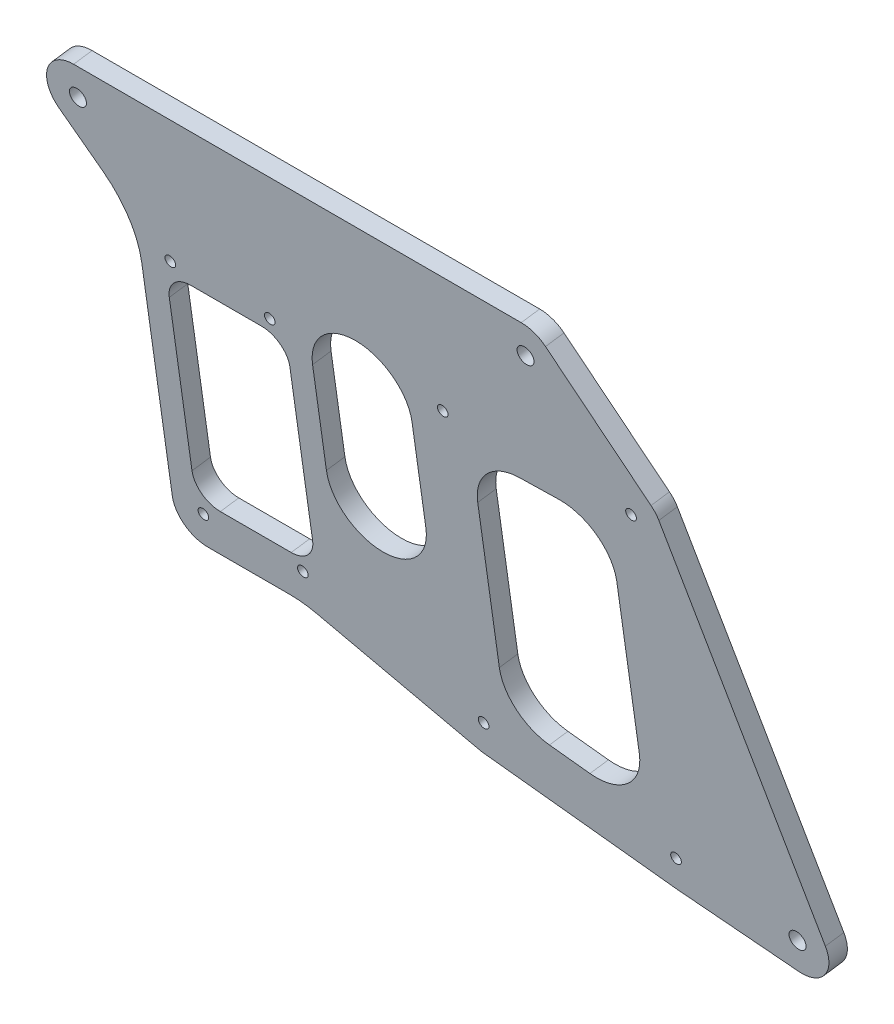
SolidWorks part; units mm, degrees
material "Acrylic (Medium-high impact)"
ref_plane "Front Plane" through (0, 0, 0) normal (0, 0, 1) x (1, 0, 0)
ref_plane "Top Plane" through (0, 0, 0) normal (0, 1, 0) x (1, 0, 0)
ref_plane "Right Plane" through (0, 0, 0) normal (1, 0, 0) x (0, 0, -1)
sketch "Sketch2" plane through (0, -851.6064, 6059.4947) normal (0, 0.1392, -0.9903) x (-1, 0, 0)
  line L1 (-291.6598, -2420.9907) -> (-107.4887, -2420.9907)
  line L2 (-291.6598, -2420.9907) -> (-291.6598, -2293.9907)
  line L3 (-291.6598, -2293.9907) -> (-107.4887, -2293.9907)
  line L4 (-107.4887, -2420.9907) -> (-107.4887, -2293.9907)
  circle A0 centre (-283.7223, -2413.0532) radius 2.1526 construction
  circle A1 centre (-115.4262, -2301.9282) radius 2.1526 construction
  dimension "D3" = 7.9375
  dimension "D2" = 7.9375
  dimension "D1" = 127
  dimension "D4" = 7.9375
extrude "Boss-Extrude1" add sketch "Sketch2" along normal blind 4.7625
hole_wizard "CSK for #6 Flat Head Machine Screw (100)1" positions "Sketch3" profile "Sketch4" countersink size "#6" standard "ANSI Inch" end condition through all
sketch "Sketch3" plane through (0, -850.9436, 6054.7786) normal (0, 0.1392, -0.9903) x (-1, 0, 0)
  circle A0 centre (-115.4262, -2301.9282) radius 2.1526 construction
  circle A1 centre (-229.7262, -2301.9282) radius 2.1527 construction
  circle A2 centre (-283.7223, -2413.0532) radius 2.1526 construction
  point P0 (-115.4262, -2301.9282)
  point P2 (-229.7262, -2301.9282)
  point P4 (-283.7223, -2413.0532)
  point P7 (0, 0)
  point P12 (0, 0)
sketch "Sketch4" plane through (115.4262, -3130.4697, 5734.4121) normal (1, 0, 0) x (0, 0.9903, 0.1392)
  line L0 (0, 0) -> (0, 22.2655)
  line L1 (0, 22.2655) -> (2.1526, 22.2655)
  line L2 (2.1526, 22.2655) -> (2.1526, 1.1669)
  line L3 (2.1526, 1.1669) -> (3.5433, 0)
  line L5 (3.5433, 0) -> (0, 0)
  line L6 (-2.1526, 1.1669) -> (-3.5433, 0) construction
  line L11 (0, -6.35) -> (0, 107.95) construction
  dimension "Thru Hole Dia." = 4.3053
  dimension "Thru Hole Depth" = 22.2655
  dimension "Near C'Sink Dia." = 7.0866
  dimension "Near C'Sink Angle" = 100
sketch "Sketch5" plane through (0, -850.9436, 6054.7786) normal (0, 0.1392, -0.9903) x (-1, 0, 0)
  line L0 (-183.275, -2361.6107) -> (-183.275, -2336.2107) construction
  line L1 (-195.975, -2361.6107) -> (-195.975, -2336.2107)
  line L2 (-170.575, -2361.6107) -> (-170.575, -2336.2107)
  line L3 (-190.775, -2361.6107) -> (-175.775, -2361.6107) construction
  arc A0 (-195.975, -2361.6107) -> (-170.575, -2361.6107) centre (-183.275, -2361.6107) ccw
  arc A1 (-170.575, -2336.2107) -> (-195.975, -2336.2107) centre (-183.275, -2336.2107) ccw
  point P2 (-183.275, -2348.9107)
  point P7 (0, 0)
  point P8 (0, 0)
  point P11 (0, 0)
  point P12 (-183.275, -2361.6107)
  dimension "D2" = 12.7
  dimension "D1" = 25.4
extrude "Cut-Extrude1" cut sketch "Sketch5" against normal through all
hole_wizard "#2 Clearance Hole1" positions "Sketch6" profile "Sketch7" hole size "#2" standard "ANSI Inch" end condition through all
sketch "Sketch6" plane through (0, -850.9436, 6054.7786) normal (0, 0.1392, -0.9903) x (-1, 0, 0)
  point P0 (-135.015, -2391.3927)
  point P3 (-160.415, -2391.3927)
  point P6 (-160.415, -2330.6867)
  point P9 (-135.015, -2330.6867)
  point P12 (-204.8641, -2328.6753)
  point P15 (-204.8641, -2403.6053)
  point P18 (-253.1241, -2409.9553)
  point P21 (-253.1241, -2327.4053)
sketch "Sketch7" plane through (135.015, -3219.0635, 5721.961) normal (1, 0, 0) x (0, 0.9903, 0.1392)
  line L0 (0, 0) -> (0, 22.2655)
  line L1 (0, 22.2655) -> (1.3525, 22.2655)
  line L2 (1.3525, 22.2655) -> (1.3525, 0)
  line L5 (1.3525, 0) -> (0, 0)
  line L11 (0, -6.35) -> (0, 107.95) construction
  dimension "Thru Hole Dia." = 2.7051
  dimension "Thru Hole Depth" = 22.2655
sketch "Sketch9" plane through (0, -850.9436, 6054.7786) normal (0, 0.1392, -0.9903) x (-1, 0, 0)
  line L0 (-291.6598, -2293.9907) -> (-291.6598, -2420.9907) construction
  line L1 (-107.4887, -2293.9907) -> (-291.6598, -2293.9907) construction
  line L2 (-107.4887, -2420.9907) -> (-107.4887, -2293.9907) construction
  line L3 (-282.9228, -2420.9504) -> (-252.3246, -2417.8525)
  line L4 (-203.8286, -2411.475) -> (-252.0886, -2417.825)
  line L5 (-159.3444, -2399.3302) -> (-202.7612, -2411.2592)
  line L6 (-135.015, -2399.3302) -> (-159.3444, -2399.3302)
  line L7 (-127.0775, -2391.3927) -> (-127.0775, -2324.8049)
  line L8 (-127.0775, -2324.8049) -> (-109.8135, -2307.5409)
  line L9 (-115.4262, -2293.9907) -> (-229.7262, -2293.9907)
  line L10 (-258.9702, -2322.0363) -> (-235.5723, -2296.5592)
  line L11 (-260.5989, -2324.7349) -> (-291.1971, -2410.3828)
  line L16 (-291.6598, -2293.9907) -> (-291.6598, -2420.9907)
  line L17 (-291.6598, -2420.9907) -> (-107.4887, -2420.9907)
  line L18 (-107.4887, -2420.9907) -> (-107.4887, -2293.9907)
  line L19 (-107.4887, -2293.9907) -> (-291.6598, -2293.9907)
  line L20 (-291.6598, -2293.9907) -> (-291.6598, -2420.9907)
  line L21 (-291.6598, -2420.9907) -> (-107.4887, -2420.9907)
  line L22 (-107.4887, -2420.9907) -> (-107.4887, -2293.9907)
  line L23 (-107.4887, -2293.9907) -> (-291.6598, -2293.9907)
  circle A0 centre (-229.7262, -2301.9282) radius 7.9375 construction
  circle A1 centre (-115.4262, -2301.9282) radius 7.9375 construction
  circle A2 centre (-283.7223, -2413.0532) radius 7.9375 construction
  circle A3 centre (-253.1241, -2327.4053) radius 7.9375 construction
  circle A4 centre (-253.1241, -2409.9553) radius 7.9375 construction
  circle A5 centre (-204.8641, -2403.6053) radius 7.9375 construction
  arc A6 (-252.0886, -2417.825) -> (-252.3246, -2417.8525) centre (-253.1241, -2409.9553) cw
  circle A7 centre (-160.415, -2391.3927) radius 7.9375 construction
  circle A8 centre (-135.015, -2391.3927) radius 7.9375 construction
  arc A9 (-202.7612, -2411.2592) -> (-203.8286, -2411.475) centre (-204.8641, -2403.6053) cw
  arc A10 (-109.8135, -2307.5409) -> (-115.4262, -2293.9907) centre (-115.4262, -2301.9282) ccw
  arc A11 (-282.9228, -2420.9504) -> (-291.1971, -2410.3828) centre (-283.7223, -2413.0532) cw
  arc A12 (-260.5989, -2324.7349) -> (-258.9702, -2322.0363) centre (-253.1241, -2327.4053) cw
  arc A13 (-229.7262, -2293.9907) -> (-235.5723, -2296.5592) centre (-229.7262, -2301.9282) ccw
  arc A14 (-135.015, -2399.3302) -> (-127.0775, -2391.3927) centre (-135.015, -2391.3927) ccw
  line M19 (-291.6598, -2293.9907) -> (-291.6598, -2420.9907)
  line M20 (-291.6598, -2420.9907) -> (-107.4887, -2420.9907)
  line M21 (-107.4887, -2420.9907) -> (-107.4887, -2293.9907)
  line M22 (-107.4887, -2293.9907) -> (-291.6598, -2293.9907)
  dimension "D1" = 15.875
  dimension "D2" = 135
  dimension "D3" = 0
extrude "Cut-Extrude2" cut sketch "Sketch9" against normal blind 4.7625 contours A14 L6 L5 A9 L4 A6 L3 A11 L21 A10 L8 L7 M21 | A13 A11 L11 A12 L10 M22 M19 | A10 L22 M22 | A11 L20 M20
fillet "Fillet1" radius 25.4 2 edges at (127.0775, -3153.4551, 5733.5863) (159.3444, -3227.2551, 5723.2144)
sketch "Sketch10" plane through (0, -850.9436, 6054.7786) normal (0, 0.1392, -0.9903) x (-1, 0, 0)
  line L0 (-127.0775, -2391.3927) -> (-127.0775, -2335.3259) construction
  line L1 (-133.4275, -2388.2177) -> (-164.225, -2388.2177)
  line L2 (-133.4275, -2388.2177) -> (-133.4275, -2333.8617)
  line L3 (-133.4275, -2333.8617) -> (-164.225, -2333.8617)
  line L4 (-164.225, -2388.2177) -> (-164.225, -2333.8617)
  line L5 (-170.575, -2361.6107) -> (-170.575, -2336.2107) construction
  circle A0 centre (-135.015, -2391.3927) radius 1.6 construction
  circle A1 centre (-135.015, -2330.6867) radius 1.3526 construction
  dimension "D2" = 3.175
  dimension "D1" = 6.35
  dimension "D3" = 3.175
  dimension "D4" = 6.35
extrude "Cut-Extrude3" cut sketch "Sketch10" against normal through all
fillet "Fillet2" radius 6.35 4 edges at (164.225, -3162.4238, 5732.3259) (133.4275, -3162.4238, 5732.3259) (133.4275, -3216.2508, 5724.761) (164.225, -3216.2508, 5724.761)
sketch "Sketch11" plane through (0, -850.9436, 6054.7786) normal (0, 0.1392, -0.9903) x (-1, 0, 0)
  line L0 (-253.1241, -2409.9553) -> (-204.8641, -2403.6053) construction
  line L1 (-204.8641, -2403.6053) -> (-204.8641, -2328.6753) construction
  line L2 (-204.8641, -2328.6753) -> (-253.1241, -2327.4053) construction
  line L3 (-253.1241, -2327.4053) -> (-253.1241, -2409.9553) construction
  line L4 (-246.7741, -2333.9246) -> (-246.7741, -2402.7151)
  line L5 (-246.7741, -2402.7151) -> (-211.2141, -2398.0361)
  line L6 (-211.2141, -2398.0361) -> (-211.2141, -2334.8604)
  line L7 (-211.2141, -2334.8604) -> (-246.7741, -2333.9246)
  circle A0 centre (-253.1241, -2409.9553) radius 7.9375 construction
  circle A1 centre (-204.8641, -2403.6053) radius 7.9375 construction
  circle A2 centre (-253.1241, -2327.4053) radius 7.9375 construction
  circle A3 centre (-204.8641, -2328.6753) radius 7.9375 construction
  dimension "D1" = 15.875
  dimension "D2" = 6.35
extrude "Cut-Extrude4" cut sketch "Sketch11" against normal through all
fillet "Fillet3" radius 12.7 4 edges at (211.2141, -3163.4128, 5732.1869) (246.7741, -3162.4861, 5732.3171) (211.2141, -3225.9736, 5723.3945) (246.7741, -3230.607, 5722.7433)
